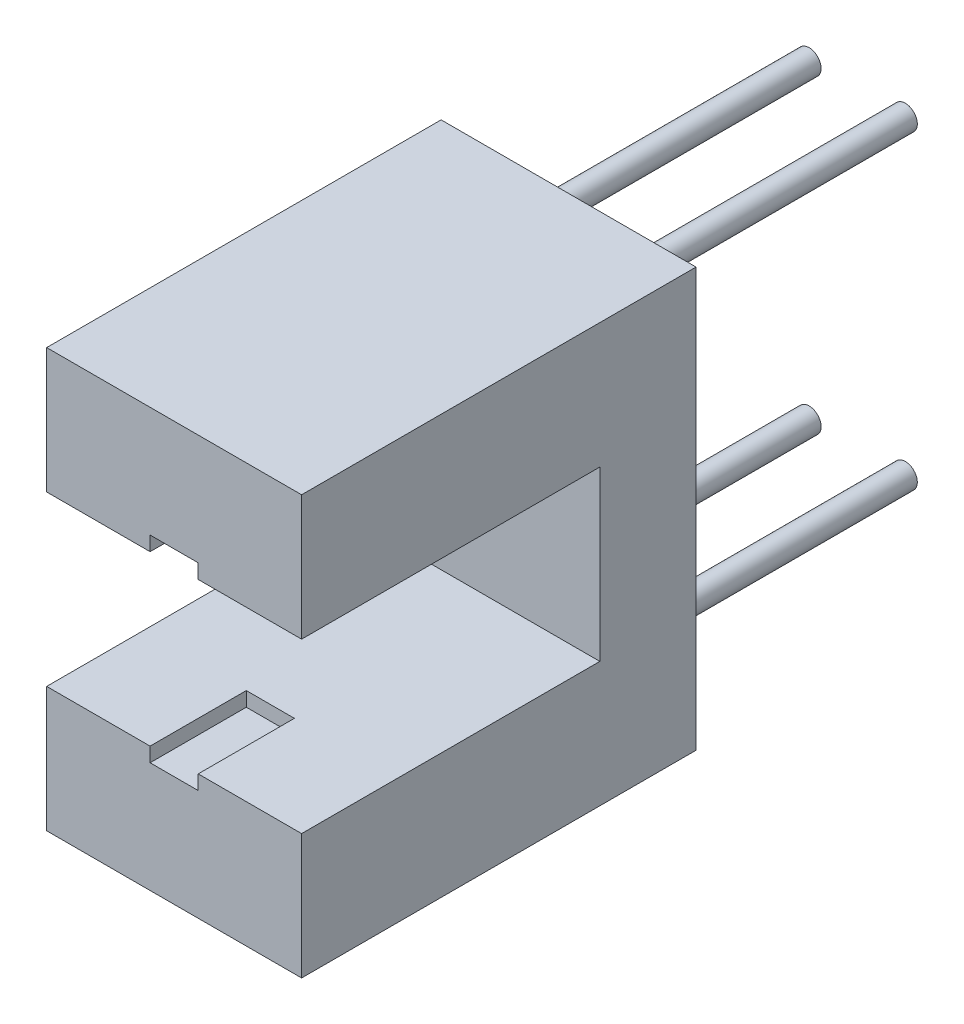
SolidWorks part; units mm, degrees
ref_plane "Front Plane" through (0, 0, 0) normal (0, 0, 1) x (1, 0, 0)
ref_plane "Top Plane" through (0, 0, 0) normal (0, 1, 0) x (1, 0, 0)
ref_plane "Right Plane" through (0, 0, 0) normal (1, 0, 0) x (0, 0, -1)
sketch "Sketch1" plane through (0, 0, 0) normal (0, 0, 1) x (1, 0, 0)
  line L0 (0, 0) -> (8.3333, 0) construction
  line L1 (2.65, 1.75) -> (-2.65, 1.75)
  line L2 (2.65, 1.75) -> (2.65, 4.35)
  line L3 (2.65, 4.35) -> (-2.65, 4.35)
  line L4 (-2.65, 1.75) -> (-2.65, 4.35)
  line L5 (2.65, 1.75) -> (-2.65, 4.35) construction
  line L6 (2.65, 4.35) -> (-2.65, 1.75) construction
  line L7 (2.65, -4.35) -> (-2.65, -1.75) construction
  line L8 (2.65, -1.75) -> (-2.65, -4.35) construction
  line L9 (-2.65, -1.75) -> (-2.65, -4.35)
  line L10 (2.65, -4.35) -> (-2.65, -4.35)
  line L11 (2.65, -1.75) -> (2.65, -4.35)
  line L12 (2.65, -1.75) -> (-2.65, -1.75)
  point P0 (0, 3.05)
  point P12 (0, -3.05)
  dimension "D1" = 5.3
  dimension "D2" = 8.7
  dimension "D3" = 2.6
  dimension "D4" = 3.5
extrude "Boss-Extrude1" add sketch "Sketch1" along normal blind 6.2
sketch "Sketch2" plane through (0, 0, 0) normal (0, 0, -1) x (-1, 0, 0)
  line L1 (2.65, -4.35) -> (-2.65, -4.35)
  line L2 (2.65, -4.35) -> (2.65, 4.35)
  line L3 (2.65, 4.35) -> (-2.65, 4.35)
  line L4 (-2.65, -4.35) -> (-2.65, 4.35)
  line L5 (2.65, -4.35) -> (-2.65, 4.35) construction
  line L6 (2.65, 4.35) -> (-2.65, -4.35) construction
  point P0 (0, 0)
extrude "Boss-Extrude2" add sketch "Sketch2" along normal blind 2
sketch "Sketch3" plane through (0, 0, 6.2) normal (0, 0, 1) x (1, 0, 0)
  line L0 (2.65, -1.75) -> (-2.65, -1.75) construction
  line L1 (0.5, -2.05) -> (-0.5, -2.05)
  line L2 (0.5, -2.05) -> (0.5, 2.05)
  line L3 (0.5, 2.05) -> (-0.5, 2.05)
  line L4 (-0.5, -2.05) -> (-0.5, 2.05)
  line L5 (0.5, -2.05) -> (-0.5, 2.05) construction
  line L6 (0.5, 2.05) -> (-0.5, -2.05) construction
  point P0 (0, 0)
  dimension "D1" = 1
  dimension "D2" = 0.3
extrude "Cut-Extrude1" cut sketch "Sketch3" against normal blind 2
sketch "Sketch4" plane through (0, 0, -2) normal (0, 0, -1) x (-1, 0, 0)
  line L0 (0, 7.0232) -> (0, -7.0232) construction
  line L1 (0, 0) -> (-7.8374, 0) construction
  line L3 (-1, -3.225) -> (1, -3.225) construction
  line L4 (-1, -3.225) -> (-1, 3.225) construction
  line L5 (-1, 3.225) -> (1, 3.225) construction
  line L6 (1, -3.225) -> (1, 3.225) construction
  line L7 (-1, -3.225) -> (1, 3.225) construction
  line L8 (-1, 3.225) -> (1, -3.225) construction
  circle A0 centre (-1, -3.225) radius 0.25
  circle A1 centre (1, -3.225) radius 0.25
  circle A2 centre (1, 3.225) radius 0.25
  circle A3 centre (-1, 3.225) radius 0.25
  point P10 (0, 0)
  point P14 (0, 0)
  point P16 (0, 0)
  point P19 (-1, -0.3405)
  point P20 (0, 0)
  point P21 (0, 0)
  point P22 (-0.9321, -3.225)
  dimension "D2" = 0.5
  dimension "D1" = 2
  dimension "D3" = 6.45
extrude "Boss-Extrude3" add sketch "Sketch4" along normal blind 6
